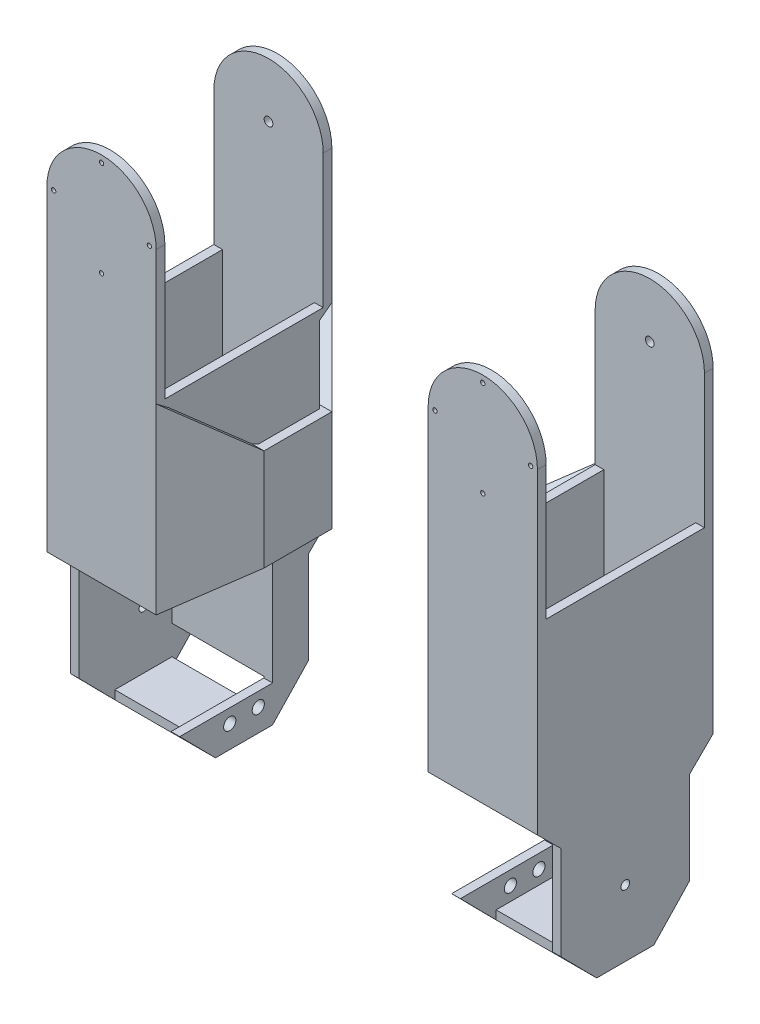
SolidWorks part; units mm, degrees
ref_plane "前视基准面" through (0, 0, 0) normal (0, 0, 1) x (1, 0, 0)
ref_plane "上视基准面" through (0, 0, 0) normal (0, 1, 0) x (1, 0, 0)
ref_plane "右视基准面" through (0, 0, 0) normal (1, 0, 0) x (0, 0, -1)
sketch "草图1" plane through (0, 0, 0) normal (0, 1, 0) x (1, 0, 0)
  line L1 (-29.9221, 16.5885) -> (1.7779, 16.5885)
  line L2 (-29.9221, 16.5885) -> (-29.9221, -38.0115)
  line L3 (-29.9221, -38.0115) -> (1.7779, -38.0115)
  line L4 (1.7779, 16.5885) -> (1.7779, -38.0115)
  line L5 (-32.9221, 19.5885) -> (4.7779, 19.5885)
  line L6 (-32.9221, 19.5885) -> (-32.9221, -41.0115)
  line L7 (-32.9221, -41.0115) -> (4.7779, -41.0115)
  line L8 (4.7779, 19.5885) -> (4.7779, -41.0115)
  dimension "D1" = 3
  dimension "D2" = 3
  dimension "D3" = 3
  dimension "D4" = 3
  dimension "D5" = 37.7
  dimension "D6" = 54.6
extrude "凸台-拉伸1" add sketch "草图1" along normal blind 60
sketch "草图2" plane through (0, 60, 0) normal (0, 1, 0) x (1, 0, 0)
  line L0 (4.7779, -41.0115) -> (4.7779, 19.5885) construction
  line L1 (-32.9221, 19.5885) -> (4.7779, 19.5885)
  line L2 (-32.9221, 19.5885) -> (-32.9221, 16.5885)
  line L3 (-32.9221, 16.5885) -> (4.7779, 16.5885)
  line L4 (4.7779, 19.5885) -> (4.7779, 16.5885)
  line L6 (-32.9221, -41.0115) -> (4.7779, -41.0115)
  line L7 (-32.9221, -41.0115) -> (-32.9221, -38.0115)
  line L8 (-32.9221, -38.0115) -> (4.7779, -38.0115)
  line L9 (4.7779, -41.0115) -> (4.7779, -38.0115)
  dimension "D1" = 3
  dimension "D2" = 3
extrude "凸台-拉伸2" add sketch "草图2" along normal blind 65
sketch "草图3" plane through (0, 0, 41.0115) normal (0, 0, 1) x (1, 0, 0)
  line L0 (-32.9221, 125) -> (4.7779, 125) construction
  line L1 (-32.9221, 125) -> (-32.9221, 0) construction
  line L2 (-32.9221, 106.15) -> (-32.9221, 125)
  line L3 (-32.9221, 125) -> (-14.0721, 125)
  line L4 (-14.0721, 125) -> (4.7779, 125)
  line L5 (4.7779, 125) -> (4.7779, 106.15)
  arc A0 (-32.9221, 106.15) -> (4.7779, 106.15) centre (-14.0721, 106.15) cw
  line M2 (4.7779, 0) -> (4.7779, 125)
  line M3 (4.7779, 125) -> (-32.9221, 125)
  line M4 (-32.9221, 125) -> (-32.9221, 0)
  dimension "D3" = 18.85
  dimension "D1" = 18.85
  dimension "D2" = 18.85
extrude "切除-拉伸1" cut sketch "草图3" against normal blind 100 contours A0 M3 M2 | A0 M4 M3
sketch "草图4" plane through (0, 0, 0) normal (0, -1, 0) x (1, 0, 0)
  line L1 (-32.9221, 41.0115) -> (4.7779, 41.0115)
  line L2 (-32.9221, 41.0115) -> (-32.9221, -19.5885)
  line L3 (-32.9221, -19.5885) -> (4.7779, -19.5885)
  line L4 (4.7779, 41.0115) -> (4.7779, -19.5885)
extrude "凸台-拉伸3" add sketch "草图4" along normal blind 3
sketch "草图5" plane through (0, -3, 0) normal (0, -1, 0) x (1, 0, 0)
  line L0 (-32.9221, -19.5885) -> (4.7779, -19.5885) construction
  line L1 (-32.9221, 41.0115) -> (-29.9221, 41.0115)
  line L2 (-32.9221, 41.0115) -> (-32.9221, -19.5885)
  line L3 (-32.9221, -19.5885) -> (-29.9221, -19.5885)
  line L4 (-29.9221, 41.0115) -> (-29.9221, -19.5885)
  line L6 (4.7779, 41.0115) -> (1.7779, 41.0115)
  line L7 (4.7779, 41.0115) -> (4.7779, -19.5885)
  line L8 (4.7779, -19.5885) -> (1.7779, -19.5885)
  line L9 (1.7779, 41.0115) -> (1.7779, -19.5885)
  dimension "D1" = 3
  dimension "D2" = 3
extrude "凸台-拉伸4" add sketch "草图5" along normal blind 60.1
sketch "草图7" plane through (4.7779, 0, 0) normal (1, 0, 0) x (0, 0, -1)
  line L0 (-32.8945, -11.05) -> (11.4715, -11.05) construction
  line L5 (11.4715, -11.05) -> (11.4715, -55.05) construction
  line L6 (11.4715, -55.05) -> (-32.8945, -55.05) construction
  line L7 (19.5885, 106.15) -> (19.5885, -63.1) construction
  line L12 (-58.0368, -90.0661) -> (-52.7283, -90.0661)
  line L13 (-58.0368, -90.0661) -> (-58.0368, -91.6521)
  line L14 (-58.0368, -91.6521) -> (-52.7283, -91.6521)
  line L15 (-52.7283, -90.0661) -> (-52.7283, -91.6521)
  line L17 (-41.0115, -63.1) -> (19.5885, -63.1) construction
  line L18 (-41.0115, -63.1) -> (-41.0115, -3) construction
  line L19 (-41.0115, -3) -> (19.5885, -3) construction
  line L20 (19.5885, -63.1) -> (19.5885, -3) construction
  line L21 (-41.0115, -3) -> (19.5885, -63.1) construction
  line L22 (19.5885, -3) -> (-41.0115, -63.1) construction
  line L23 (-32.8945, -55.05) -> (-32.8945, -11.05) construction
  line L24 (-32.8945, -33.05) -> (-32.8945, -11.05)
  line L25 (-32.8945, -11.05) -> (-41.0115, -3)
  line L26 (-41.0115, -3) -> (-41.0115, -63.1)
  line L28 (19.5885, -63.1) -> (19.5885, -3)
  line L29 (19.5885, -3) -> (11.4715, -11.05)
  line L30 (11.4715, -11.05) -> (11.4715, -33.05)
  line L31 (-32.8945, -33.05) -> (-32.8945, -63.1)
  line L32 (-41.0115, -63.1) -> (-32.8945, -63.1)
  line L33 (11.4715, -63.1) -> (11.4715, -33.05)
  line L34 (11.4715, -63.1) -> (19.5885, -63.1)
  dimension "D1" = 60.1
  dimension "D2" = 44
extrude "切除-拉伸2" cut sketch "草图7" against normal blind 52 contours L30 L24 L25 L26 L28 L29
sketch "草图9" plane through (4.7779, 0, 0) normal (1, 0, 0) x (0, 0, -1)
  line L1 (-20.5615, -23.2) -> (-0.8615, -23.2) construction
  line L2 (-20.5615, 4.05) -> (-0.8615, 4.05) construction
  line L3 (-20.5615, 4.05) -> (-20.5615, -50.45) construction
  line L4 (-20.5615, -50.45) -> (-0.8615, -50.45) construction
  line L5 (-0.8615, 4.05) -> (-0.8615, -50.45) construction
  line L6 (-41.0115, -3) -> (19.5885, -3) construction
  line L7 (-20.5615, -43.4) -> (-0.8615, -43.4)
  line L8 (-20.5615, -43.4) -> (-20.5615, -3)
  line L9 (-20.5615, -3) -> (-0.8615, -3)
  line L10 (-0.8615, -43.4) -> (-0.8615, -3)
  circle A3 centre (-15.6365, -48.16) radius 2.1
  circle A4 centre (-5.7865, -48.16) radius 2.1
  circle A5 centre (-5.7865, 1.76) radius 2.1
  circle A6 centre (-15.6365, 1.76) radius 2.1
  dimension "D7" = 4.2
  dimension "D8" = 4.2
  dimension "D2" = 7.05
  dimension "D4" = 54.5
  dimension "D5" = 2.29
  dimension "D6" = 4.925
  dimension "D9" = 4.925
  dimension "D10" = 2.29
  dimension "D11" = 49.92
  dimension "D12" = 4.76
  dimension "D13" = 4.76
extrude "切除-拉伸4" cut sketch "草图9" against normal blind 3
sketch "草图10" plane through (0, -3, 0) normal (0, -1, 0) x (1, 0, 0)
  line L0 (-29.9221, -19.5885) -> (-29.9221, 41.0115) construction
  line L1 (-29.9221, 38.0115) -> (1.7779, 38.0115)
  line L2 (-29.9221, 38.0115) -> (-29.9221, -16.5885)
  line L3 (-29.9221, -16.5885) -> (1.7779, -16.5885)
  line L4 (1.7779, 38.0115) -> (1.7779, -16.5885)
  line L5 (1.7779, -19.5885) -> (1.7779, -11.4715) construction
  line L6 (1.7779, 41.0115) -> (-29.9221, 41.0115) construction
  line L7 (-29.9221, -19.5885) -> (1.7779, -19.5885) construction
  dimension "D1" = 3
  dimension "D2" = 3
extrude "切除-拉伸5" cut sketch "草图10" against normal blind 3
sketch "草图11" plane through (-32.9221, 0, 0) normal (-1, 0, 0) x (0, 0, 1)
  line L0 (-11.4715, -11.05) -> (-11.4715, -63.1) construction
  arc A0 (-11.4715, -33.05) -> (32.8945, -33.05) centre (10.7115, -33.05) ccw construction
  circle A2 centre (10.7115, -33.05) radius 1.5
  dimension "D1" = 3
extrude "切除-拉伸6" cut sketch "草图11" against normal blind 3
sketch "草图14" plane through (0, 60, 0) normal (0, 1, 0) x (1, 0, 0)
  line L0 (4.7779, 19.5885) -> (4.7779, -41.0115)
  line L1 (4.7779, -41.0115) -> (23.3779, -22.4115)
  line L2 (23.3779, -22.4115) -> (23.3779, 0.9885)
  line L3 (23.3779, 0.9885) -> (4.7779, 19.5885)
  line L4 (4.7779, 15.3458) -> (20.3779, -0.2542)
  line L5 (20.3779, -0.2542) -> (20.3779, -21.1689)
  line L6 (20.3779, -21.1689) -> (4.7779, -36.7689)
  line M9 (4.7779, -38.0115) -> (4.7779, 16.5885)
  dimension "D1" = 15.6
  dimension "D3" = 45
  dimension "D4" = 45
  dimension "D5" = 3
  dimension "D6" = 3
  dimension "D7" = 3
extrude "凸台-拉伸6" add sketch "草图14" against normal blind 63 contours L5 L6 L0 L1 L2 L3 L4 M9
sketch "草图15" plane through (23.3779, 0, 0) normal (1, 0, 0) x (0, 0, -1)
  line L0 (-22.4115, 11) -> (0.9885, 11)
  line L1 (-22.4115, -3) -> (-22.4115, 60) construction
  line L2 (0.9885, -3) -> (0.9885, 60) construction
  line L3 (0.9885, 11) -> (19.5885, -3)
  line L4 (19.5885, -3) -> (-41.0115, -3)
  line L5 (-41.0115, -3) -> (-22.4115, 11)
  line L6 (-41.0115, 60) -> (19.5885, 60)
  line L7 (19.5885, -3) -> (19.5885, 60) construction
  line L8 (19.5885, 60) -> (0.9885, 46)
  line L9 (0.9885, 46) -> (-22.4115, 46)
  line L10 (-22.4115, 46) -> (-41.0115, 60)
  dimension "D1" = 14
  dimension "D2" = 14
extrude "切除-拉伸7" cut sketch "草图15" against normal blind 18.6
sketch "草图16" plane through (0, 0, 41.0115) normal (0, 0, 1) x (1, 0, 0)
  circle A0 centre (-14.0721, 106.15) radius 18.85 construction
  circle A1 centre (-14.0721, 106.15) radius 16.5 construction
  circle A2 centre (-14.0721, 122.65) radius 0.75
  circle A3 centre (2.4279, 106.15) radius 0.75
  circle A4 centre (-30.5721, 106.15) radius 0.75
  circle A5 centre (-14.0721, 89.65) radius 0.75
  dimension "D1" = 33
  dimension "D2" = 1.5
  dimension "D3" = 1.5
  dimension "D4" = 1.5
  dimension "D5" = 1.5
extrude "切除-拉伸8" cut sketch "草图16" against normal blind 3
sketch "草图17" plane through (0, 0, -19.5885) normal (0, 0, -1) x (-1, 0, 0)
  circle A0 centre (14.0721, 106.15) radius 18.85 construction
  circle A1 centre (14.0721, 106.15) radius 1.5
  dimension "D1" = 3
extrude "切除-拉伸9" cut sketch "草图17" against normal blind 3
ref_plane "基准面1" through (51.6779, 0, 0) normal (1, 0, 0) x (0, 0, -1)
mirror "镜向2" about plane through (51.6779, 0, 0) normal (1, 0, 0) of bodies 119
sketch "草图21" plane through (4.7779, 0, 0) normal (1, 0, 0) x (0, 0, -1)
  line L1 (-41.0115, -3) -> (-20.5615, -3)
  line L2 (-41.0115, -3) -> (-41.0115, -43.4)
  line L3 (-41.0115, -43.4) -> (-20.5615, -43.4)
  line L4 (-20.5615, -3) -> (-20.5615, -43.4)
extrude "切除-拉伸10" cut sketch "草图21" against normal blind 10
sketch "草图22" plane through (4.7779, 0, 0) normal (1, 0, 0) x (0, 0, -1)
  line L0 (-0.8615, -3) -> (-41.0115, -3) construction
  line L2 (-0.8615, -3) -> (2.1385, -3)
  line L3 (-0.8615, -3) -> (-0.8615, -42.9)
  line L4 (-0.8615, -42.9) -> (2.1385, -42.9)
  line L5 (2.1385, -3) -> (2.1385, -42.9)
  circle A0 centre (-15.6365, 1.76) radius 2.1 construction
  dimension "D1" = 4.76
  dimension "D2" = 3
extrude "凸台-拉伸7" add sketch "草图22" against normal blind 35
sketch "草图23" plane through (4.7779, 0, 0) normal (1, 0, 0) x (0, 0, -1)
  line L0 (-20.5615, -43.4) -> (-20.5615, -63.1) construction
  line L1 (-32.8945, -43.4) -> (-0.8615, -43.4) construction
  line L2 (11.4715, -63.1) -> (-32.8945, -63.1) construction
  line L3 (-0.8615, -43.4) -> (-0.8615, -63.1) construction
  line L4 (-32.8945, -43.4) -> (-20.5615, -55.92)
  line L9 (-20.5615, -52.92) -> (-0.8615, -52.92)
  line L10 (-20.5615, -52.92) -> (-20.5615, -55.92)
  line L11 (-20.5615, -55.92) -> (-0.8615, -55.92)
  line L12 (-0.8615, -52.92) -> (-0.8615, -55.92)
  line L13 (-32.8945, -43.4) -> (-32.8945, -63.1)
  line L14 (-32.8945, -63.1) -> (11.4715, -63.1)
  line L15 (11.4715, -63.1) -> (11.4715, -42.9)
  line L16 (11.4715, -11.05) -> (11.4715, -63.1) construction
  line L17 (11.4715, -42.9) -> (-0.8615, -55.92)
  line L18 (-20.5615, -55.92) -> (-0.8615, -55.92)
  circle A0 centre (-15.6365, -48.16) radius 2.1 construction
  circle A1 centre (-5.7865, -48.16) radius 2.1 construction
  line M6 (-32.8945, -43.4) -> (-32.8945, -63.1)
  line M7 (-32.8945, -63.1) -> (11.4715, -63.1)
  line M8 (11.4715, -63.1) -> (11.4715, -11.05)
  dimension "D2" = 4.925
  dimension "D3" = 4.925
  dimension "D5" = 4.76
  dimension "D1" = 19.7
  dimension "D4" = 9.52
  dimension "D6" = 3
extrude "切除-拉伸11" cut sketch "草图23" against normal blind 39 contours L17 L11 L4 M8 M6 M7
sketch "草图24" plane through (4.7779, 0, 0) normal (1, 0, 0) x (0, 0, -1)
  line L1 (-20.5615, -55.92) -> (-0.8615, -55.92)
  line L2 (-20.5615, -55.92) -> (-20.5615, -52.92)
  line L3 (-20.5615, -52.92) -> (-0.8615, -52.92)
  line L4 (-0.8615, -55.92) -> (-0.8615, -52.92)
  dimension "D1" = 3
extrude "凸台-拉伸8" add sketch "草图24" against normal blind 36
delete or keep bodies "实体-删除/保留 2" type delete bodies bodies 120
mirror "镜向6" about plane through (51.6779, 0, 0) normal (1, 0, 0) of bodies 124
